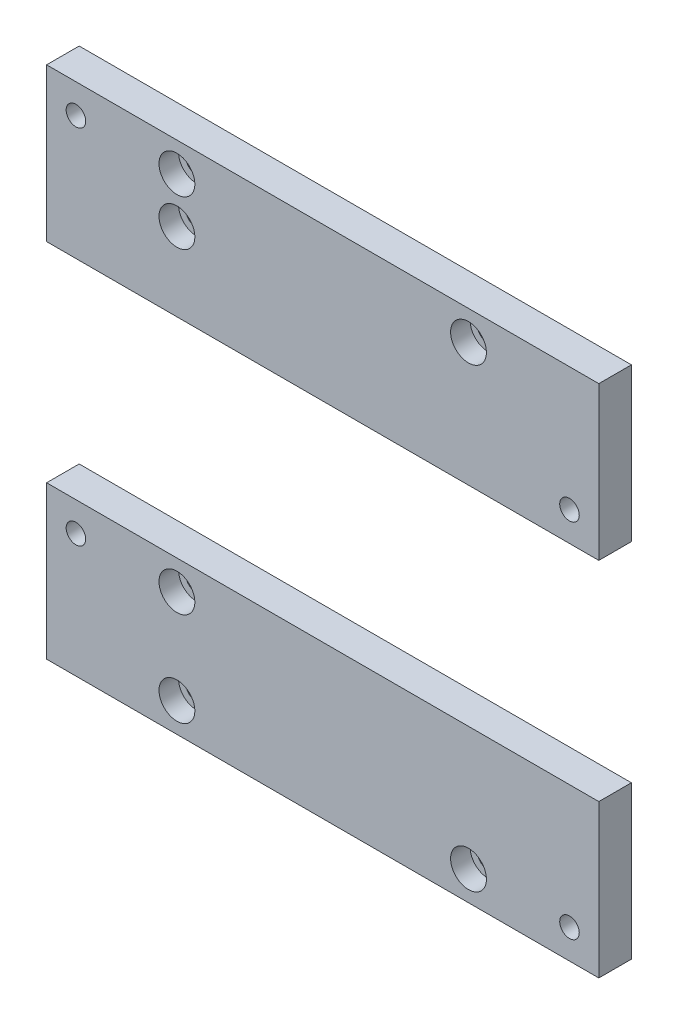
SolidWorks part; units mm, degrees
ref_plane "FP" through (0, 0, 0) normal (0, 0, 1) x (1, 0, 0)
ref_plane "TP" through (0, 0, 0) normal (0, 1, 0) x (1, 0, 0)
ref_plane "RP" through (0, 0, 0) normal (1, 0, 0) x (0, 0, -1)
sketch "Sketch2" plane through (0, 0, 0) normal (0, 0, 1) x (1, 0, 0)
  line L0 (-50, -79) -> (-50, 79) construction
  line L1 (-50, -32.1) -> (119.5, -32.1)
  line L2 (-50, -32.1) -> (-50, -79)
  line L3 (-50, -79) -> (119.5, -79)
  line L4 (119.5, -32.1) -> (119.5, -79)
  line L5 (119.5, 79) -> (119.5, -79) construction
  line L6 (-50, 79) -> (119.5, 79)
  line L7 (-50, 79) -> (-50, 32)
  line L8 (-50, 32) -> (119.5, 32)
  line L9 (119.5, 79) -> (119.5, 32)
  line L10 (-14.5, -32) -> (14.5, -32) construction
  line L11 (-14.5, 32) -> (-29.5, 32) construction
  line L12 (-50, 79) -> (119.5, 79) construction
  dimension "D1" = 0.1
extrude "Boss-Extrude1" add sketch "Sketch2" along normal blind 10
hole_wizard "CBORE for M6 SHCS1" positions "Sketch3" profile "Sketch4" counterbore size "M6" standard "ANSI Metric" end condition through all
sketch "Sketch3" plane through (0, 0, 10) normal (0, 0, 1) x (0.9063, -0.4226, 0)
  point P0 (101.6347, -29.8434)
  point P1 (20.5202, -67.6677)
  point P2 (8.3065, -41.4754)
sketch "Sketch4" plane through (79.5, -70, 10) normal (1, 0, 0) x (0, -1, 0)
  line L0 (0, 0) -> (0, 10)
  line L1 (0, 10) -> (3.3, 10)
  line L2 (3.3, 10) -> (3.3, 6)
  line L3 (3.3, 6) -> (5.5, 6)
  line L4 (5.5, 6) -> (5.5, 0)
  line L5 (5.5, 0) -> (0, 0)
  line L6 (0, -6.35) -> (0, 107.95) construction
  dimension "Thru Hole Dia." = 6.6
  dimension "Thru Hole Depth" = 10
  dimension "C'Bore Dia." = 11
  dimension "C'Bore Depth" = 6
hole_wizard "CBORE for M6 SHCS2" positions "Sketch5" profile "Sketch6" counterbore size "M6" standard "ANSI Metric" end condition through all
sketch "Sketch5" plane through (0, 0, 10) normal (0, 0, 1) x (0.9063, -0.4226, 0)
  point P0 (42.4682, 97.0397)
  point P1 (-32.7297, 46.5271)
  point P2 (-38.6464, 59.2154)
sketch "Sketch6" plane through (79.5, 70, 10) normal (1, 0, 0) x (0, -1, 0)
  line L0 (0, 0) -> (0, 10)
  line L1 (0, 10) -> (3.3, 10)
  line L3 (3.3, 10) -> (3.3, 6)
  line L4 (3.3, 6) -> (5.5, 6)
  line L5 (5.5, 6) -> (5.5, 0)
  line L7 (5.5, 0) -> (0, 0)
  line L11 (0, -6.35) -> (0, 107.95) construction
  dimension "Thru Hole Dia." = 6.6
  dimension "Thru Hole Depth" = 10
  dimension "C'Bore Dia." = 11
  dimension "C'Bore Depth" = 6
hole_wizard "Ø6.0mm Clearance Dowel Hole1" positions "Sketch7" profile "Sketch8" hole size "Ø6.0" standard "ANSI Metric" end condition through all
sketch "Sketch7" plane through (0, 0, 10) normal (0, 0, 1) x (0.9063, -0.4226, 0)
  point P0 (-66.7419, 46.1142)
  point P1 (82.8197, 83.8579)
sketch "Sketch8" plane through (-41, 70, 10) normal (1, 0, 0) x (0, -1, 0)
  line L0 (0, 0) -> (0, 10)
  line L1 (0, 10) -> (3, 10)
  line L2 (3, 10) -> (3, 0)
  line L3 (3, 0) -> (0, 0)
  line L4 (0, -6.35) -> (0, 107.95) construction
  dimension "Thru Hole Dia." = 6
  dimension "Thru Hole Depth" = 10
hole_wizard "Ø6.0mm Clearance Dowel Hole2" positions "Sketch9" profile "Sketch10" hole size "Ø6.0" standard "ANSI Metric" end condition through all
sketch "Sketch9" plane through (0, 0, 10) normal (0, 0, 1) x (0.9063, -0.4226, 0)
  point P0 (-19.789, -54.5766)
  point P1 (129.7303, -16.7422)
sketch "Sketch10" plane through (-41, -41.1, 10) normal (1, 0, 0) x (0, -1, 0)
  line L0 (0, 0) -> (0, 10)
  line L1 (0, 10) -> (3, 10)
  line L2 (3, 10) -> (3, 0)
  line L3 (3, 0) -> (0, 0)
  line L4 (0, -6.35) -> (0, 107.95) construction
  dimension "Thru Hole Dia." = 6
  dimension "Thru Hole Depth" = 10
